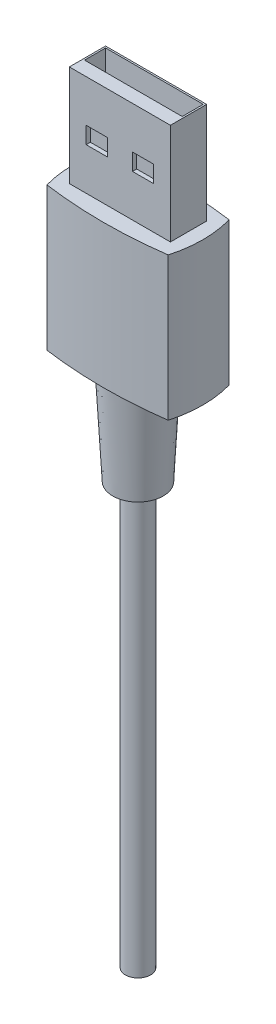
SolidWorks part; units mm, degrees
ref_plane "Front Plane" through (0, 0, 0) normal (0, 0, 1) x (1, 0, 0)
ref_plane "Top Plane" through (0, 0, 0) normal (0, 1, 0) x (1, 0, 0)
ref_plane "Right Plane" through (0, 0, 0) normal (1, 0, 0) x (0, 0, -1)
sketch "Sketch1" plane through (0, 0, 0) normal (0, 1, 0) x (1, 0, 0)
  circle A0 centre (0, 0) radius 1.5
extrude "Boss-Extrude1" add sketch "Sketch1" along normal blind 50
sketch "Sketch2" plane through (0, 50, 0) normal (0, 1, 0) x (1, 0, 0)
  circle A0 centre (0, 0) radius 3.0017
extrude "Boss-Extrude2" add sketch "Sketch2" along normal blind 11.7 draft 3 contours A0 draft outward yes
sketch "Sketch4" plane through (0, 61.7, 0) normal (0, 1, 0) x (1, 0, 0)
  line L1 (-7.2, 3.6148) -> (7.2, 3.6148)
  line L2 (-7.2, -3.6148) -> (7.2, -3.6148)
  line L4 (-7.2, 3.6148) -> (-7.2, -3.6148)
  line L5 (7.2, 3.6148) -> (7.2, -3.6148)
  circle A3 centre (0, 0) radius 3.6148 construction
  point P5 (0, 0)
  point P9 (0, 3.6148)
  point P12 (0, -3.6148)
  dimension "D3" = 7.2297
  dimension "D1" = 14.4
  dimension "D2" = 14.4
sketch "Sketch9" plane through (0, 61.7, 0) normal (0, 1, 0) x (1, 0, 0)
  line L0 (7.2, 3.6148) -> (7.2, -3.6148) construction
  line L1 (-7.2, 3.6148) -> (-7.2, -3.6148) construction
  arc A0 (-7.2, 3.6148) -> (7.2, 3.6148) centre (0, -47.9752) cw
  arc A1 (-7.2, -3.6148) -> (7.2, -3.6148) centre (0, 47.9752) ccw
  arc A2 (7.2, 3.6148) -> (7.2, -3.6148) centre (-5.6171, 0) cw
  arc A3 (-7.2, -3.6148) -> (-7.2, 3.6148) centre (5.6171, 0) cw
  point P12 (0, 4.1148)
  point P15 (0, -4.1148)
  point P16 (7.7, 0)
  point P19 (-7.7, 0)
  dimension "D4" = 0.5
  dimension "D1" = 0.5
  dimension "D2" = 0.5
  dimension "D3" = 0.5
extrude "Boss-Extrude3" add sketch "Sketch9" along normal blind 17
sketch "Sketch10" plane through (0, 78.7, 0) normal (0, 1, 0) x (1, 0, 0)
  line L1 (-6, -2.15) -> (6, -2.15)
  line L2 (-6, -2.15) -> (-6, 2.15)
  line L3 (-6, 2.15) -> (6, 2.15)
  line L4 (6, -2.15) -> (6, 2.15)
  line L5 (-6, -2.15) -> (6, 2.15) construction
  line L6 (-6, 2.15) -> (6, -2.15) construction
  point P0 (0, 0)
  dimension "D1" = 12
  dimension "D2" = 4.3
extrude "Boss-Extrude4" add sketch "Sketch10" along normal blind 12
sketch "Sketch11" plane through (0, 90.7, 0) normal (0, 1, 0) x (1, 0, 0)
  line L0 (-6, -2.15) -> (6, -2.15) construction
  line L1 (-5.8, -0.55) -> (5.8, -0.55)
  line L2 (-5.8, -0.55) -> (-5.8, 1.95)
  line L3 (-5.8, 1.95) -> (5.8, 1.95)
  line L4 (5.8, -0.55) -> (5.8, 1.95)
  line L5 (6, -2.15) -> (6, 2.15) construction
  line L6 (-6, 2.15) -> (-6, -2.15) construction
  line L7 (6, 2.15) -> (-6, 2.15) construction
  point P6 (0, -0.55)
  point P7 (5.8, 0.7)
  point P10 (-5.8, 0.7)
  point P13 (0, 1.95)
  dimension "D1" = 1.6
  dimension "D2" = 0.2
  dimension "D3" = 0.2
  dimension "D4" = 0.2
extrude "Cut-Extrude1" cut sketch "Sketch11" against normal blind 12
sketch "Sketch12" plane through (0, 0, 2.15) normal (0, 0, 1) x (1, 0, 0)
  line L1 (-6, 90.7) -> (6, 90.7) construction
  line L3 (-6, 90.7) -> (-6, 78.7) construction
  line L7 (-4, 85.7) -> (-1.5, 85.7)
  line L8 (-4, 85.7) -> (-4, 83.7)
  line L9 (-4, 83.7) -> (-1.5, 83.7)
  line L10 (-1.5, 85.7) -> (-1.5, 83.7)
  line L14 (4, 83.7) -> (1.5, 83.7)
  line L15 (1.5, 85.7) -> (1.5, 83.7)
  line L16 (4, 85.7) -> (1.5, 85.7)
  line L17 (4, 85.7) -> (4, 83.7)
  dimension "D1" = 2
  dimension "D2" = 5
  dimension "D3" = 2
  dimension "D4" = 2.5
extrude "Cut-Extrude2" cut sketch "Sketch12" against normal blind 0.5
sketch "Sketch13" plane through (0, 0, 2.15) normal (0, 0, 1) x (1, 0, 0)
  line L0 (0, 78.7) -> (0, 80.2)
  line L1 (7.2, 78.7) -> (-7.2, 78.7) construction
  line L2 (-6, 90.7) -> (6, 90.7) construction
  line L3 (0, 80.2) -> (1.2, 80.2)
  line L4 (0, 81.7) -> (0, 87.7)
  line L5 (1.2, 81.7) -> (0, 81.7)
  line L6 (0, 87.7) -> (1.2, 87.7)
  line L7 (0, 89.2) -> (0, 90.7)
  line L8 (1.2, 89.2) -> (0, 89.2)
  arc A0 (1.2, 89.2) -> (1.2, 87.7) centre (-0.8709, 88.45) cw
  arc A1 (1.2, 81.7) -> (1.2, 80.2) centre (-0.8713, 80.95) cw
  dimension "D1" = 6
  dimension "D2" = 1.5
  dimension "D3" = 1.5
  dimension "D4" = 1.2
  dimension "D5" = 1.2
  dimension "D6" = 1.5
sketch "Sketch14" plane through (0, 0, -2.15) normal (0, 0, -1) x (-1, 0, 0)
  line L0 (-6, 90.7) -> (6, 90.7) construction
  line L1 (-4, 83.7) -> (-1.5, 83.7)
  line L2 (-4, 83.7) -> (-4, 85.7)
  line L3 (-4, 85.7) -> (-1.5, 85.7)
  line L4 (-1.5, 83.7) -> (-1.5, 85.7)
  line L10 (-6, 90.7) -> (-6, 78.7) construction
  line L13 (4, 85.7) -> (1.5, 85.7)
  line L14 (1.5, 83.7) -> (1.5, 85.7)
  line L15 (4, 83.7) -> (1.5, 83.7)
  line L16 (4, 83.7) -> (4, 85.7)
  dimension "D1" = 2.5
  dimension "D2" = 2
  dimension "D3" = 5
  dimension "D4" = 2
extrude "Cut-Extrude4" cut sketch "Sketch14" against normal blind 0.5
sketch "Sketch16" plane through (0, 0, -2.15) normal (0, 0, -1) x (-1, 0, 0)
  ellipse E0 centre (0, 80.9426) end of major axis (0.9507, 80.9426) minor radius 0.481
extrude "Cut-Extrude5" cut sketch "Sketch16" against normal blind 0.5 draft 22
